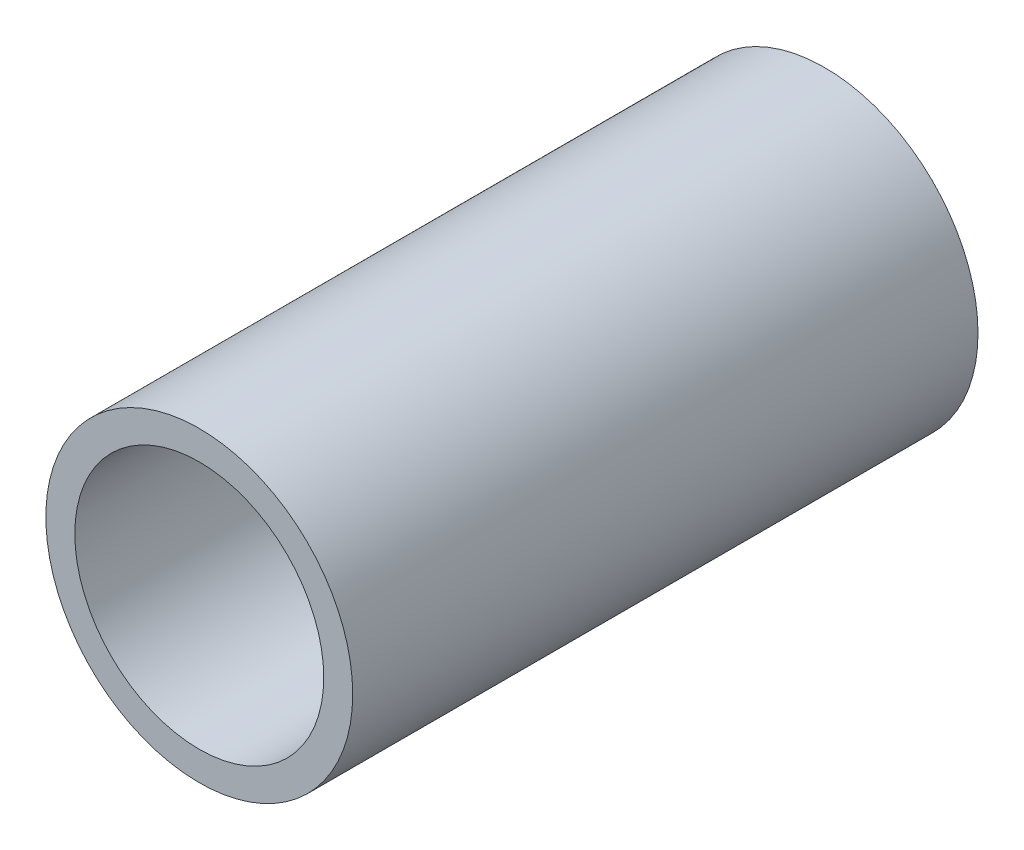
SolidWorks part; units mm, degrees
ref_plane "Front Plane" through (0, 0, 0) normal (0, 0, 1) x (1, 0, 0)
ref_plane "Top Plane" through (0, 0, 0) normal (0, 1, 0) x (1, 0, 0)
ref_plane "Right Plane" through (0, 0, 0) normal (1, 0, 0) x (0, 0, -1)
sketch "Sketch1" plane through (0, 0, 0) normal (0, 0, 1) x (1, 0, 0)
  circle A0 centre (0, 0) radius 21.5
  circle A1 centre (0, 0) radius 26.5
extrude "Boss-Extrude1" add sketch "Sketch1" along normal blind 108
